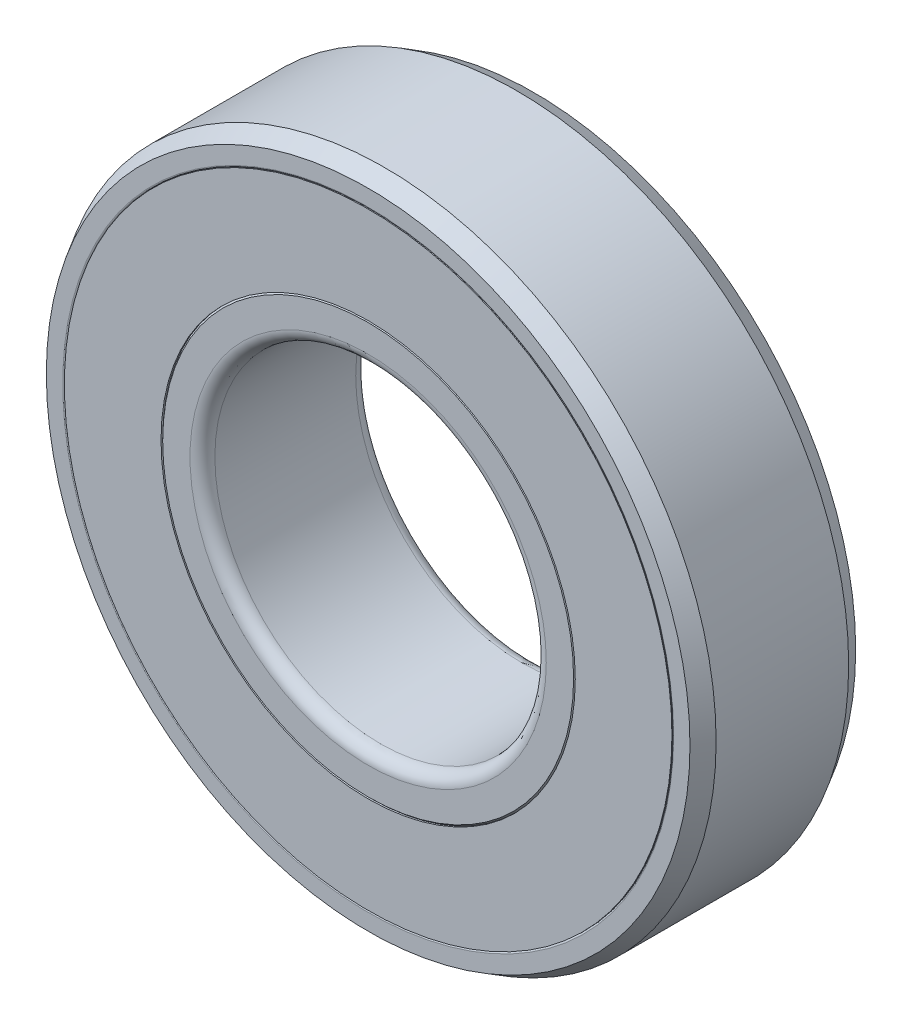
SolidWorks part; units mm, degrees
ref_plane "Front Plane" through (0, 0, 0) normal (0, 0, 1) x (1, 0, 0)
ref_plane "Top Plane" through (0, 0, 0) normal (0, 1, 0) x (1, 0, 0)
ref_plane "Right Plane" through (0, 0, 0) normal (1, 0, 0) x (0, 0, -1)
sketch "Sketch1" plane through (0, 0, 0) normal (0, 0, 1) x (1, 0, 0)
  line L0 (0, 6) -> (0, 8) construction
  line L1 (0, 4) -> (0, 6) construction
  line L2 (0, 8) -> (0, 7.3333) construction
  line L3 (0, 7.3333) -> (0, 6.6667) construction
  line L4 (0, 6.6667) -> (0, 6) construction
  circle A0 centre (0, 0) radius 4
  circle A1 centre (0, 0) radius 8
  circle A2 centre (0, 0) radius 7.3333 construction
  circle A4 centre (0, 0) radius 5 construction
  point P6 (0, 5)
  dimension "OD" = 16
  dimension "ID" = 8
sketch "Sketch2" plane through (0, 0, 0) normal (1, 0, 0) x (0, 0, -1)
  line L0 (-2, 8) -> (2, 8) construction
  line L1 (2, 8) -> (2, -8) construction
  line L2 (2, 0) -> (-2, 0) construction
  line L3 (-2, 4) -> (-2, -4) construction
  point P2 (0, 8)
  dimension "Width" = 4
  dimension "For Shaft Diameter" = 8
  dimension "For Housing ID" = 16
sketch "Sketch3" plane through (0, 0, 0) normal (1, 0, 0) x (0, 0, -1)
  line L0 (-1.6, -8) -> (1.6, -8)
  line L3 (-2, -7.3733) -> (-2, -7.7691)
  line L4 (0, -5) -> (0, -7.3333) construction
  line L5 (-1.6, -8) -> (-2, -7.7691)
  line L6 (-1.7, -4) -> (1.7, -4)
  line L7 (-1.1111, -7.3333) -> (-1.1111, -7.5556) construction
  line L8 (-1.96, -5) -> (-1.1111, -5)
  line L9 (-2, -5) -> (0, -5) construction
  line L11 (-2, -7.3333) -> (-2, -5) construction
  line L12 (-2, -4.96) -> (-2, -4.3)
  line L14 (-2, 0) -> (2, 0) construction
  line L15 (-1.96, -7.3333) -> (-1.1111, -7.3333)
  line L17 (0, 0) -> (0, -8) construction
  line L18 (-1.1111, -7.5556) -> (-1.1111, -7.7778) construction
  line L19 (1.6, -8) -> (2, -7.7691)
  line L20 (0, -7.3333) -> (-2, -7.3333) construction
  line L21 (-2, 4) -> (-2, -4) construction
  line L22 (-1.1111, -7.7778) -> (-1.1111, -8) construction
  line L30 (-2, -4.96) -> (-1.96, -5)
  line L31 (1.96, -5) -> (1.1111, -5)
  line L32 (2, -4.96) -> (1.96, -5)
  line L33 (2, -4.96) -> (2, -4.3)
  line L34 (1.96, -7.3333) -> (1.1111, -7.3333)
  line L35 (2, -7.3733) -> (2, -7.7691)
  line L36 (0, 8) -> (0, -8) construction
  arc A0 (0, -4.5556) -> (0, -7.7778) centre (0, -6.1667) ccw construction
  arc A1 (-1.1111, -5) -> (1.1111, -5) centre (0, -6.1667) cw
  arc A2 (-1.1111, -7.3333) -> (1.1111, -7.3333) centre (0, -6.1667) ccw
  arc A4 (-1.96, -7.3333) -> (-2, -7.3733) centre (-1.96, -7.3733) ccw
  arc A5 (-1.7, -4) -> (-2, -4.3) centre (-1.7, -4.3) ccw
  arc A6 (1.7, -4) -> (2, -4.3) centre (1.7, -4.3) cw
  arc A7 (1.96, -7.3333) -> (2, -7.3733) centre (1.96, -7.3733) cw
  point P28 (0, -6.1667)
  point P46 (-2, -4)
  point P54 (0, -4)
  dimension "D4" = 0.04
  dimension "D7" = 0.3
  dimension "D5" = 45
  dimension "D6" = 0.04
  dimension "D3" = 0.4
  dimension "D2" = 60
revolve "Revolve1" add sketch "Sketch3" angle 360 about L14
sketch "Sketch4" plane through (0, 0, 0) normal (1, 0, 0) x (0, 0, -1)
  line L0 (-1.96, -7.3333) -> (-1.1111, -7.3333) construction
  line L1 (-2, -5) -> (-1.7083, -5)
  line L2 (-2, -5) -> (-2, -7.3333)
  line L3 (-2, -7.3333) -> (-1.7083, -7.3333)
  line L4 (-1.7083, -5) -> (-1.7083, -7.3333)
  line L5 (-2, -4.96) -> (-2, -4.3) construction
  line L6 (-2, -6.1667) -> (-1.9028, -6.1667) construction
  line L7 (-1.9028, -6.1667) -> (-1.8056, -6.1667) construction
  line L8 (-1.8056, -6.1667) -> (-1.7083, -6.1667) construction
  line L9 (-1.7083, -6.1667) -> (-1.6111, -6.1667) construction
  line L10 (-2, -7.3333) -> (-2, -5) construction
  line L11 (-1.96, -5) -> (-1.1111, -5) construction
  arc A1 (0, -4.5556) -> (0, -7.7778) centre (0, -6.1667) ccw construction
revolve "Revolve2" add sketch "Sketch4" angle 360 about L14
sketch "Sketch5" plane through (0, 0, 0) normal (1, 0, 0) x (0, 0, -1)
  line L2 (0, -4.5556) -> (0, -7.7778)
  arc A2 (0, -7.7778) -> (0, -4.5556) centre (0, -6.1667) cw
revolve "Revolve3" add sketch "Sketch5" angle 360 about L17
pattern_circular "CirPattern1" count 7 over 360 about axis through (0, 0, 0) along (0, 0, 1) of bodies 138
equation "\"D4@Sketch3\"=\"Width@Sketch2\"*.01"
equation "\"D6@Sketch3\"=\"Width@Sketch2\"*.01"
equation "\"D7@Sketch3\"=\"Width@Sketch2\"*.075"
equation "\"D3@Sketch3\"=\"Width@Sketch2\"*.1"
